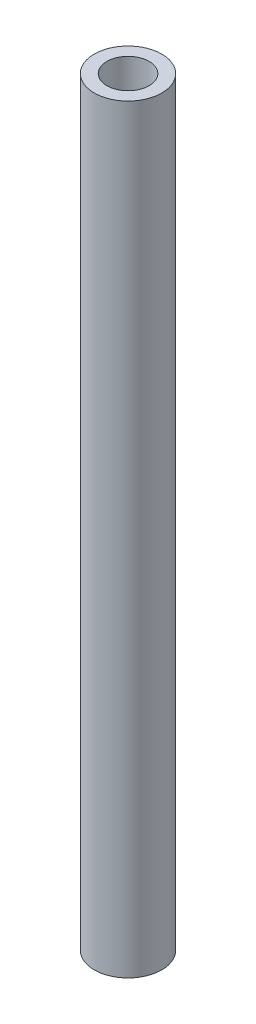
SolidWorks part; units mm, degrees
ref_plane "Płaszczyzna przednia" through (0, 0, 0) normal (0, 0, 1) x (1, 0, 0)
ref_plane "Płaszczyzna górna" through (0, 0, 0) normal (0, 1, 0) x (1, 0, 0)
ref_plane "Płaszczyzna prawa" through (0, 0, 0) normal (1, 0, 0) x (0, 0, -1)
sketch "Szkic1" plane through (0, 0, 0) normal (0, 1, 0) x (1, 0, 0)
  circle A0 centre (0, 0) radius 2.5
  circle A1 centre (0, 0) radius 4
  dimension "D1" = 5
  dimension "D2" = 8
extrude "Dodanie-wyciągnięcie1" add sketch "Szkic1" along normal blind 90
